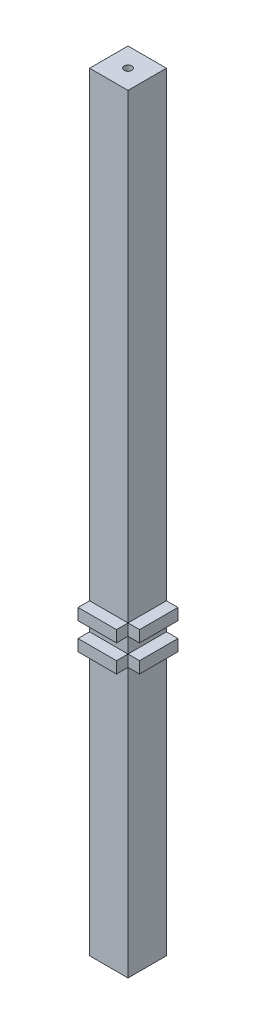
SolidWorks part; units mm, degrees
ref_plane "Płaszczyzna przednia" through (0, 0, 0) normal (0, 0, 1) x (1, 0, 0)
ref_plane "Płaszczyzna górna" through (0, 0, 0) normal (0, 1, 0) x (1, 0, 0)
ref_plane "Płaszczyzna prawa" through (0, 0, 0) normal (1, 0, 0) x (0, 0, -1)
sketch "Szkic1" plane through (0, 0, 0) normal (0, 1, 0) x (1, 0, 0)
  line L1 (-5, -5) -> (5, -5)
  line L2 (-5, -5) -> (-5, 5)
  line L3 (-5, 5) -> (5, 5)
  line L4 (5, -5) -> (5, 5)
  line L5 (-5, -5) -> (5, 5) construction
  line L6 (-5, 5) -> (5, -5) construction
  point P0 (0, 0)
  dimension "D1" = 10
  dimension "D2" = 10
extrude "Dodanie-wyciągnięcie1" add sketch "Szkic1" along normal blind 200
sketch "Szkic2" plane through (0, 200, 0) normal (0, 1, 0) x (1, 0, 0)
  circle A0 centre (0, 0) radius 1
  dimension "D1" = 2
extrude "Wytnij-wyciągnięcie1" cut sketch "Szkic2" against normal blind 10
sketch "Szkic3" plane through (0, 0, 0) normal (0, -1, 0) x (1, 0, 0)
  circle A0 centre (0, 0) radius 1 construction
  circle A1 centre (0, 0) radius 1
extrude "Wytnij-wyciągnięcie2" cut sketch "Szkic3" against normal blind 10
sketch "Szkic4" plane through (0, 0, 5) normal (0, 0, 1) x (1, 0, 0)
  line L0 (-5, 70) -> (5, 70) construction
  line L1 (-5, 200) -> (-5, 0) construction
  line L2 (5, 200) -> (5, 0) construction
  line L3 (-5, 0) -> (5, 0) construction
  line L5 (-5, 70) -> (5, 70)
  line L6 (-5, 70) -> (-5, 73)
  line L7 (-5, 73) -> (5, 73)
  line L8 (5, 70) -> (5, 73)
  line L9 (-5, 77) -> (5, 77)
  line L10 (-5, 77) -> (-5, 80)
  line L11 (-5, 80) -> (5, 80)
  line L12 (5, 77) -> (5, 80)
  dimension "D1" = 70
  dimension "D2" = 3
  dimension "D3" = 4
  dimension "D4" = 3
extrude "Dodanie-wyciągnięcie2" add sketch "Szkic4" along normal blind 3
sketch "Szkic6" plane through (5, 0, 0) normal (1, 0, 0) x (0, 0, -1)
  line L0 (5, 200) -> (5, 0) construction
  line L1 (-5, 70) -> (5, 70)
  line L2 (-5, 70) -> (-5, 73)
  line L3 (-5, 73) -> (5, 73)
  line L4 (5, 70) -> (5, 73)
  line L6 (-5, 77) -> (5, 77)
  line L7 (-5, 77) -> (-5, 80)
  line L8 (-5, 80) -> (5, 80)
  line L9 (5, 77) -> (5, 80)
  dimension "D1" = 3
  dimension "D2" = 3
extrude "Dodanie-wyciągnięcie3" add sketch "Szkic6" along normal blind 3
